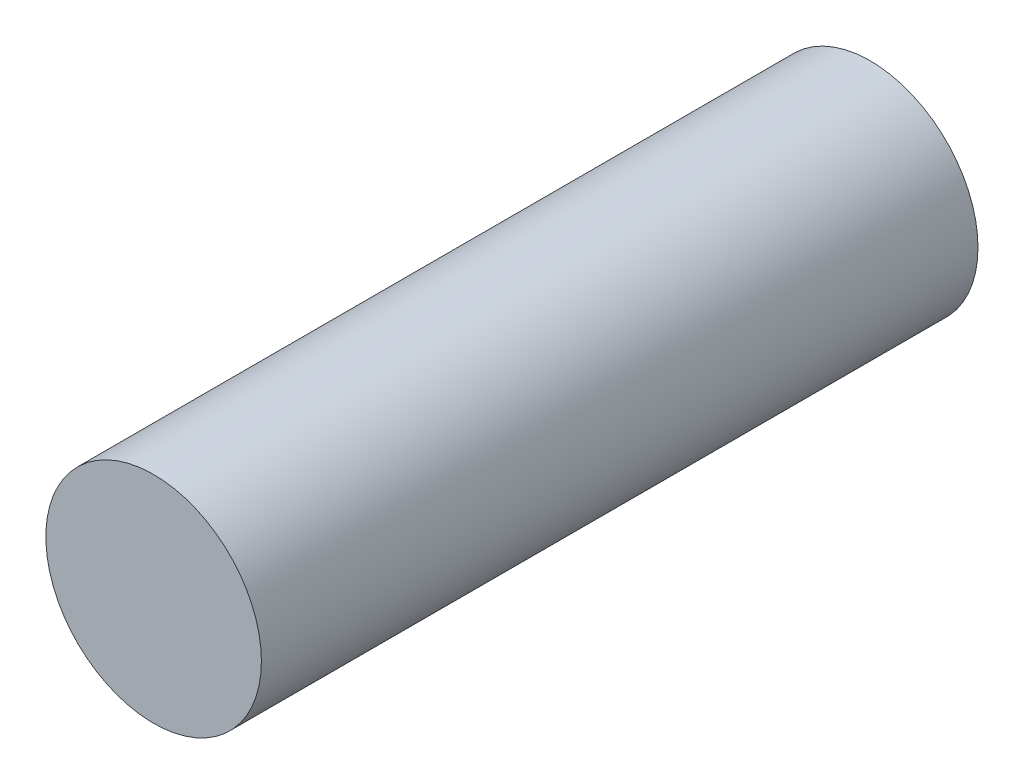
SolidWorks part; units mm, degrees
ref_plane "Alzado" through (0, 0, 0) normal (0, 0, 1) x (1, 0, 0)
ref_plane "Planta" through (0, 0, 0) normal (0, 1, 0) x (1, 0, 0)
ref_plane "Vista lateral" through (0, 0, 0) normal (1, 0, 0) x (0, 0, -1)
sketch "Croquis1" plane through (0, 0, 0) normal (0, 0, 1) x (1, 0, 0)
  circle A0 centre (0, 0) radius 37
extrude "Saliente-Extruir1" add sketch "Croquis1" along normal blind 246
